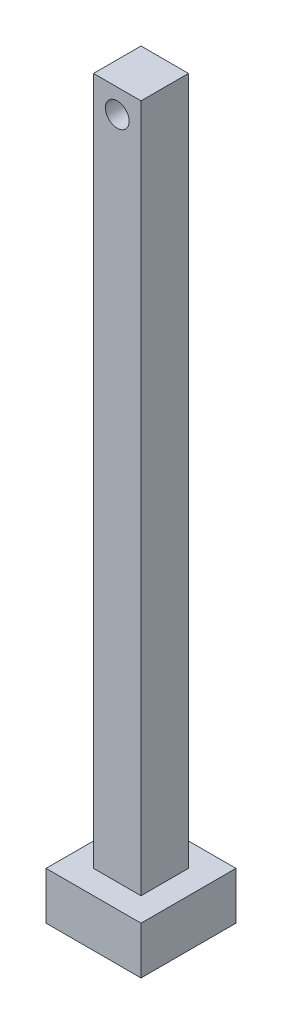
SolidWorks part; units mm, degrees
ref_plane "Front Plane" through (0, 0, 0) normal (0, 0, 1) x (1, 0, 0)
ref_plane "Top Plane" through (0, 0, 0) normal (0, 1, 0) x (1, 0, 0)
ref_plane "Right Plane" through (0, 0, 0) normal (1, 0, 0) x (0, 0, -1)
sketch "Sketch1" plane through (0, 0, 0) normal (0, 0, 1) x (1, 0, 0)
  line L1 (0, 0) -> (20, 0)
  line L2 (0, 0) -> (0, 300)
  line L3 (0, 300) -> (20, 300)
  line L4 (20, 0) -> (20, 300)
  circle A0 centre (10, 290) radius 5
  dimension "D3" = 10
  dimension "D1" = 300
  dimension "D2" = 20
  dimension "D4" = 10
  dimension "D5" = 10
extrude "Boss-Extrude2" add sketch "Sketch1" along normal mid plane 20
sketch "Sketch5" plane through (0, 0, 0) normal (0, 1, 0) x (1, 0, 0)
  line L0 (20, 10) -> (0, 10) construction
  line L1 (-10, 20) -> (30, 20)
  line L2 (-10, 20) -> (-10, -20)
  line L3 (-10, -20) -> (30, -20)
  line L4 (30, 20) -> (30, -20)
  line L6 (0, -10) -> (0, 10) construction
  dimension "D1" = 40
  dimension "D2" = 40
  dimension "D3" = 10
  dimension "D4" = 10
extrude "Boss-Extrude3" add sketch "Sketch5" along normal mid plane 20
